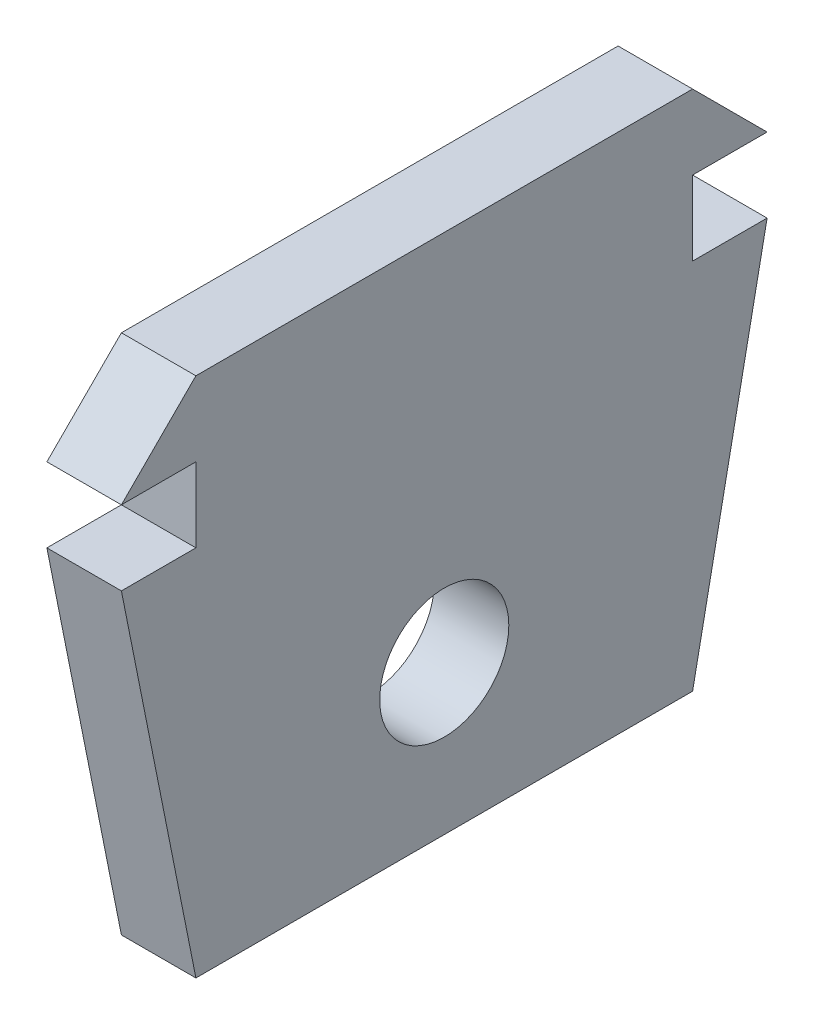
SolidWorks part; units mm, degrees
ref_plane "Plan de face" through (0, 0, 0) normal (0, 0, 1) x (1, 0, 0)
ref_plane "Plan de dessus" through (0, 0, 0) normal (0, 1, 0) x (1, 0, 0)
ref_plane "Plan de droite" through (0, 0, 0) normal (1, 0, 0) x (0, 0, -1)
sketch "Esquisse4" plane through (0, 0, 0) normal (1, 0, 0) x (0, 0, -1)
  line L0 (-20, 0) -> (0, 0)
  line L1 (0, 0) -> (3, 15)
  line L2 (3, 15) -> (0, 15)
  line L3 (0, 15) -> (0, 18)
  line L4 (0, 18) -> (3, 18)
  line L5 (3, 18) -> (0, 21)
  line L6 (0, 21) -> (-20, 21)
  line L7 (-20, 21) -> (-23, 18)
  line L8 (-23, 18) -> (-20, 18)
  line L9 (-20, 18) -> (-20, 15)
  line L11 (-20, 15) -> (-23, 15)
  line L12 (-23, 15) -> (-20, 0)
  circle A0 centre (-10, 6) radius 2.6
  dimension "D11" = 5.2
  dimension "D13" = 10
  dimension "D1" = 3
  dimension "D2" = 3
  dimension "D3" = 3
  dimension "D4" = 3
  dimension "D5" = 3
  dimension "D6" = 3
  dimension "D7" = 15
  dimension "D8" = 20
  dimension "D9" = 15
  dimension "D10" = 3
  dimension "D12" = 6
extrude "Boss.-Extru.2" add sketch "Esquisse4" along normal blind 3
